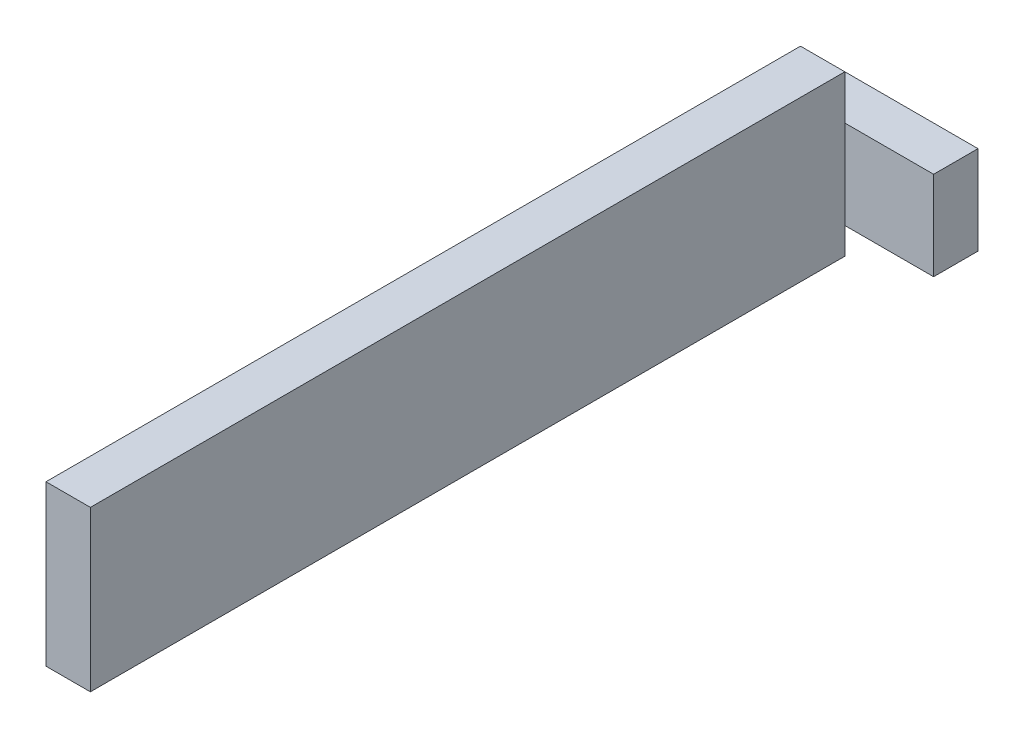
SolidWorks part; units mm, degrees
ref_plane "Front Plane" through (0, 0, 0) normal (0, 0, 1) x (1, 0, 0)
ref_plane "Top Plane" through (0, 0, 0) normal (0, 1, 0) x (1, 0, 0)
ref_plane "Right Plane" through (0, 0, 0) normal (1, 0, 0) x (0, 0, -1)
sketch "Sketch1" plane through (0, 0, 0) normal (0, 1, 0) x (1, 0, 0)
  line L0 (0, 0) -> (-10, 0)
  line L1 (-10, 0) -> (-10, -90)
  line L2 (-10, -90) -> (-5, -90)
  line L3 (-5, -90) -> (-5, -5)
  line L4 (-5, -5) -> (0, -5)
  line L5 (0, -5) -> (5, -5)
  line L6 (5, -5) -> (5, 0)
  line L9 (0, 0) -> (5, 0)
  dimension "D1" = 10
  dimension "D2" = 90
  dimension "D3" = 85
  dimension "D4" = 5
  dimension "D5" = 5
  dimension "D7" = 5
extrude "Boss-Extrude1" add sketch "Sketch1" along normal blind 10
ref_plane "Plane1" through (0, 10, 0) normal (0, 1, 0) x (1, 0, 0)
sketch "Sketch3" plane through (0, 10, 0) normal (0, 1, 0) x (1, 0, 0)
  line L1 (-10, -90) -> (-5, -90)
  line L2 (-10, -90) -> (-10, -5)
  line L3 (-10, -5) -> (-5, -5)
  line L4 (-5, -90) -> (-5, -5)
extrude "Boss-Extrude2" add sketch "Sketch3" along normal blind 5
ref_plane "Plane2" through (0, 0, 0) normal (0, -1, 0) x (-1, 0, 0)
sketch "Sketch5" plane through (0, 0, 0) normal (0, -1, 0) x (-1, 0, 0)
  line L1 (5, -5) -> (10, -5)
  line L2 (5, -5) -> (5, -90)
  line L3 (5, -90) -> (10, -90)
  line L4 (10, -5) -> (10, -90)
extrude "Boss-Extrude4" add sketch "Sketch5" along normal blind 3
